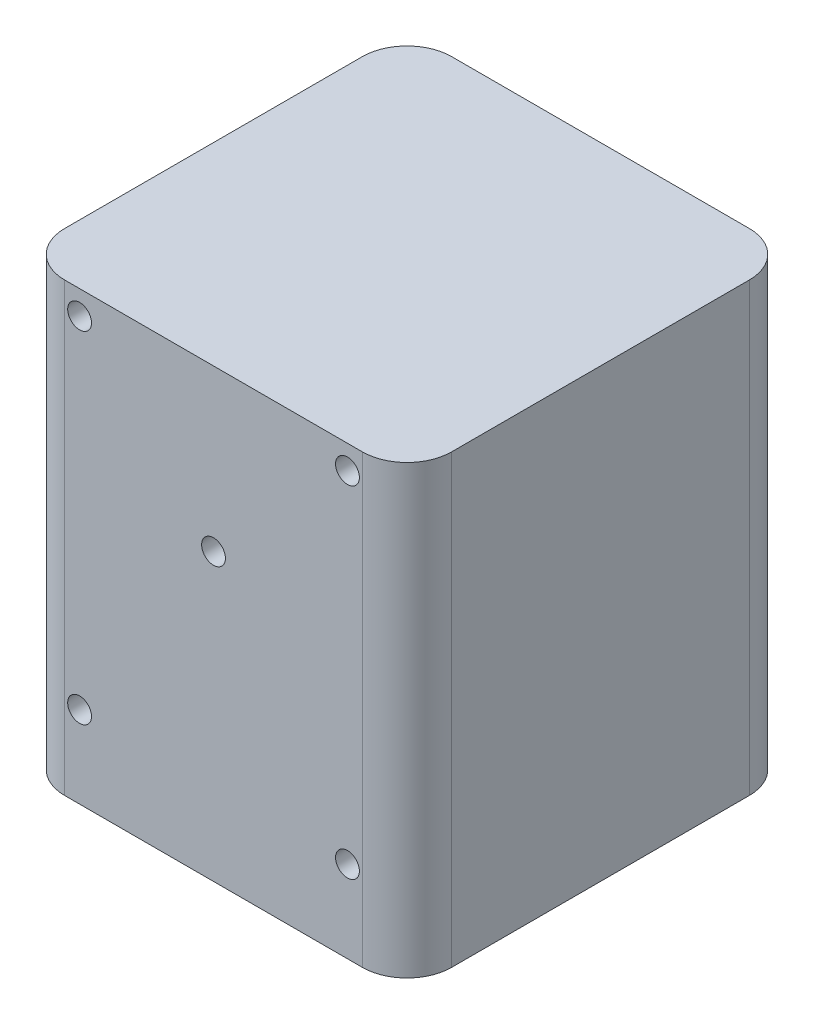
SolidWorks part; units mm, degrees
ref_plane "Front Plane" through (0, 0, 0) normal (0, 0, 1) x (1, 0, 0)
ref_plane "Top Plane" through (0, 0, 0) normal (0, 1, 0) x (1, 0, 0)
ref_plane "Right Plane" through (0, 0, 0) normal (1, 0, 0) x (0, 0, -1)
sketch "Sketch1" plane through (0, 0, 0) normal (0, 1, 0) x (1, 0, 0)
  line L1 (-13, 13) -> (13, 13)
  line L2 (-13, 13) -> (-13, -13)
  line L3 (-13, -13) -> (13, -13)
  line L4 (13, 13) -> (13, -13)
  line L5 (-13, 13) -> (13, -13) construction
  line L6 (-13, -13) -> (13, 13) construction
  point P0 (0, 0)
  dimension "D1" = 26
extrude "Boss-Extrude1" add sketch "Sketch1" along normal mid plane 30
fillet "Fillet1" radius 3 4 edges at (-13, 0, -13) (13, 0, -13) (-13, 0, 13) (13, 0, 13)
sketch "Sketch2" plane through (0, -15, 0) normal (0, -1, 0) x (1, 0, 0)
  circle A0 centre (0, 0) radius 12
extrude "Cut-Extrude1" cut sketch "Sketch2" against normal blind 10
hole_wizard "M2 Tapped Hole2" positions "Sketch3" profile "Sketch4" tap size "M2" standard "ISO"
sketch "Sketch3" plane through (0, 0, 13) normal (0, 0, 1) x (1, 0, 0)
  line L0 (0, -44.7868) -> (0, 44.7868) construction
  line L2 (-10, -15) -> (10, -15) construction
  point P0 (-9, 13.4)
  point P2 (9, 13.4)
  point P4 (0, 4.2)
  point P8 (-9, -9.5)
  point P10 (9, -9.5)
  dimension "D1" = 18
  dimension "D2" = 9
  dimension "D3" = 22.9
  dimension "D4" = 13.7
  dimension "D5" = 5.5
sketch "Sketch4" plane through (-9, 13.4, 13) normal (1, 0, 0) x (0, -1, 0)
  line L0 (0, 0) -> (0, 2.9807)
  line L1 (0, 2.9807) -> (0.8, 2.5)
  line L2 (0.8, 2.5) -> (0.8, 0)
  line L5 (0.8, 0) -> (0, 0)
  line L10 (0, 2.9807) -> (-0.8, 2.5) construction
  line L11 (0, -6.35) -> (0, 107.95) construction
  dimension "Tap Drill Dia." = 1.6
  dimension "Tap Drill Depth" = 2.5
  dimension "Drill Angle" = 118
cosmetic thread "Hole Thread1" parameters "D1"=2.5, "D2"=2
cosmetic thread "Hole Thread2" parameters "D1"=2.5, "D2"=2
cosmetic thread "Hole Thread3" parameters "D1"=2.5, "D2"=2
cosmetic thread "Hole Thread4" parameters "D1"=2.5, "D2"=2
cosmetic thread "Hole Thread5" parameters "D1"=2.5, "D2"=2
mirror "Mirror1" about plane through (0, 0, 0) normal (0, 0, 1) of "M2 Tapped Hole2"
